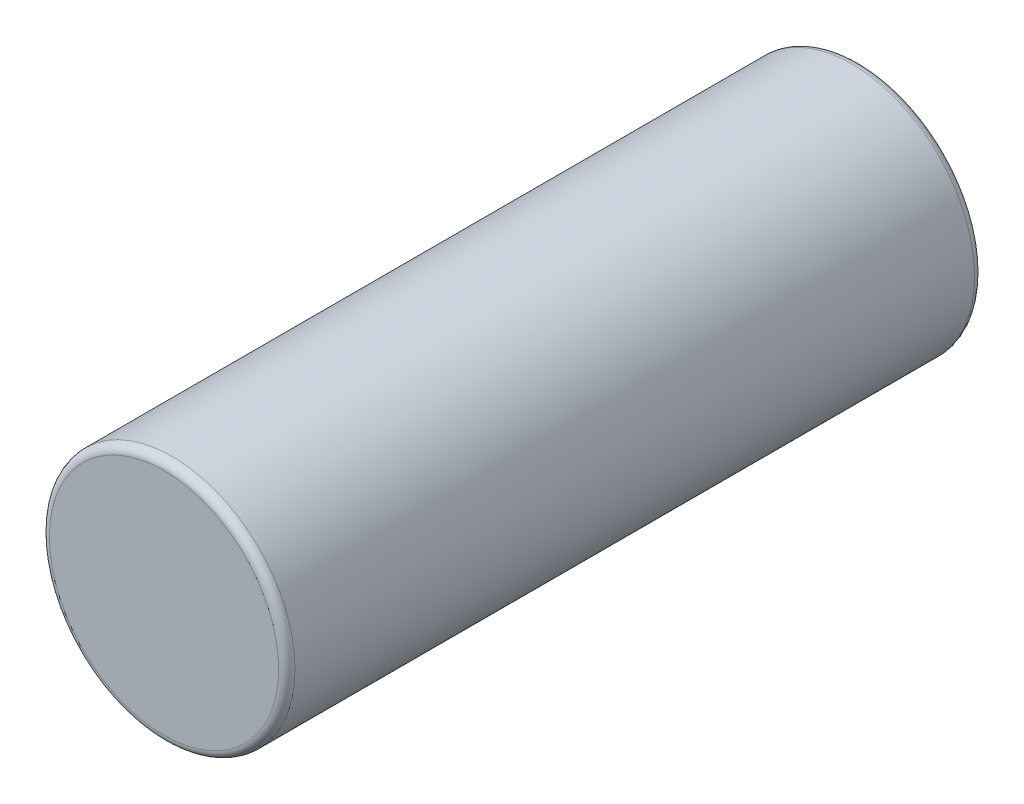
SolidWorks part; units mm, degrees
ref_plane "Plan de face" through (0, 0, 0) normal (0, 0, 1) x (1, 0, 0)
ref_plane "Plan de dessus" through (0, 0, 0) normal (0, 1, 0) x (1, 0, 0)
ref_plane "Plan de droite" through (0, 0, 0) normal (1, 0, 0) x (0, 0, -1)
sketch "Esquisse1" plane through (0, 0, 0) normal (0, 0, 1) x (1, 0, 0)
  circle A0 centre (0, 0) radius 1.5
  dimension "D1" = 3
extrude "Extrusion1" add sketch "Esquisse1" along normal blind 8.5
fillet "Congé1" radius 0.1 2 edges at (1.5, 0, 8.5) (1.5, 0, 0)
